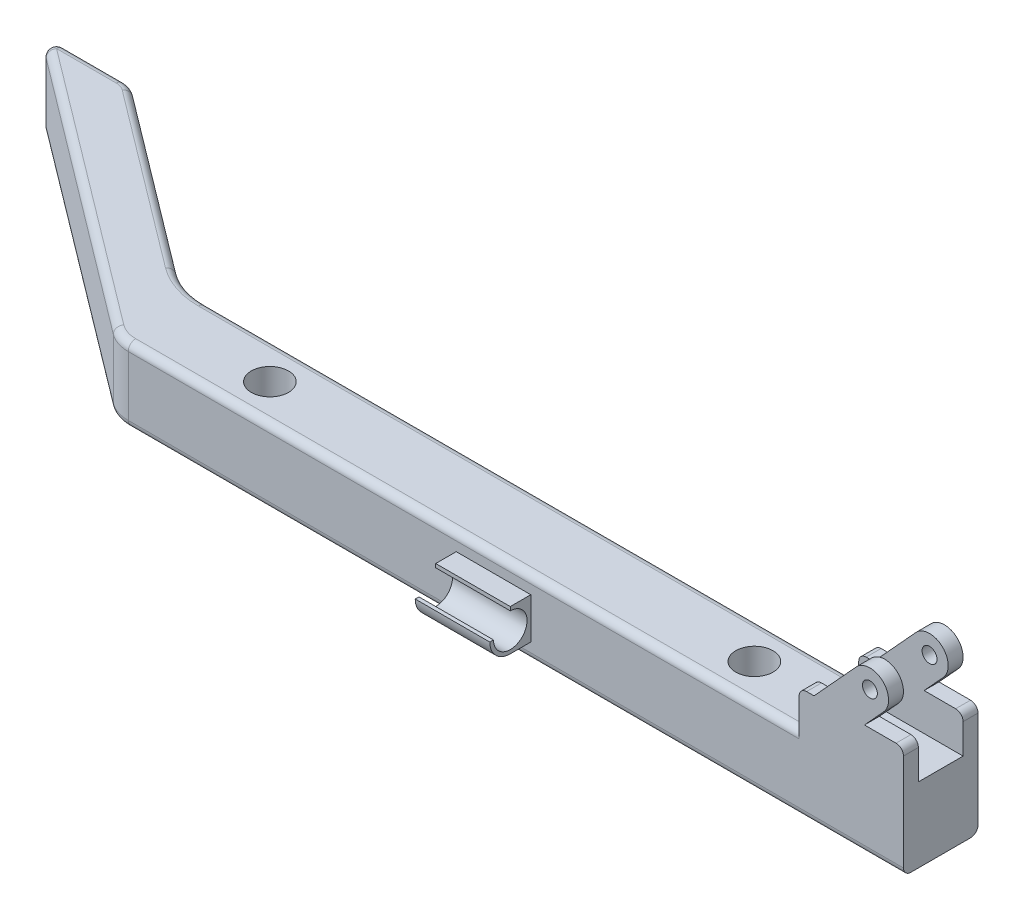
SolidWorks part; units mm, degrees
ref_plane "Front Plane" through (0, 0, 0) normal (0, 0, 1) x (1, 0, 0)
ref_plane "Top Plane" through (0, 0, 0) normal (0, 1, 0) x (1, 0, 0)
ref_plane "Right Plane" through (0, 0, 0) normal (1, 0, 0) x (0, 0, -1)
sketch "Sketch1" plane through (0, 0, 0) normal (0, 1, 0) x (1, 0, 0)
  line L0 (-49, 0) -> (49, 0)
  line L1 (-52.0091, 1.0069) -> (-88.6132, 28.5908)
  line L2 (-88.0114, 30.3894) -> (-80.0038, 30.3894)
  line L3 (-78.1983, 29.7853) -> (-54.6153, 12.0137)
  line L4 (-48.5971, 10) -> (49, 10)
  line L5 (49, 10) -> (55, 10)
  line L6 (49, 0) -> (55, 0)
  line L7 (55, 0) -> (55, 10)
  arc A0 (-52.0091, 1.0069) -> (-49, 0) centre (-49, 5) ccw
  arc A1 (-48.5971, 10) -> (-54.6153, 12.0137) centre (-48.5971, 20) cw
  arc A2 (-88.6132, 28.5908) -> (-88.0114, 30.3894) centre (-88.0114, 29.3894) cw
  arc A3 (-80.0038, 30.3894) -> (-78.1983, 29.7853) centre (-80.0038, 27.3894) cw
  point P4 (0, 0)
  point P14 (-91, 30.3894)
  point P18 (-79, 30.3894)
  dimension "D2" = 10
  dimension "D3" = 42
  dimension "D5" = 10
  dimension "D7" = 1
  dimension "D8" = 3
  dimension "D9" = 5
  dimension "D1" = 98
  dimension "D4" = 10
  dimension "D6" = 12
  dimension "D10" = 37.001
  dimension "D11" = 6
extrude "Boss-Extrude2" add sketch "Sketch1" along normal mid plane 10
sketch "Sketch3" plane through (0, 0, 0) normal (0, 0, 1) x (1, 0, 0)
  line L10 (-49, 5) -> (55, 5) construction
  line L19 (41, 5) -> (55, 5)
  line L21 (41, 5) -> (55, 5)
  line L22 (41, 5) -> (41, 10)
  line L23 (41, 10) -> (55, 10)
  line L24 (55, 5) -> (55, 10)
  line L25 (43, 10) -> (53, 10)
  line L26 (43, 10) -> (43, 17)
  line L27 (43, 17) -> (53, 17)
  line L28 (53, 10) -> (53, 17)
  dimension "D2" = 5
  dimension "D3" = 14
  dimension "D4" = 7
  dimension "D5" = 10
  dimension "D11" = 2
extrude "Boss-Extrude3" add sketch "Sketch3" against normal blind 2 contours L19 L24 L23 L22 | L23 L28 L27 L26
sketch "Sketch4" plane through (0, 0, 0) normal (0, 0, 1) x (1, 0, 0)
  line L8 (41, 10) -> (43, 10) construction
  line L9 (41, 5) -> (41, 10) construction
  line L13 (55, 10) -> (55, -5) construction
  line L14 (53, 10) -> (55, 10) construction
  line L16 (53, 10) -> (53, 17) construction
  line L17 (43, 17) -> (53, 17) construction
  line L18 (43, 10) -> (43, 17) construction
  line L19 (42, 10) -> (43, 10)
  line L20 (41, 5) -> (41, 9)
  line L21 (55, 9) -> (55, -5)
  line L22 (53, 10) -> (54, 10)
  line L23 (53, 10) -> (53, 17)
  line L24 (43, 17) -> (53, 17)
  line L25 (43, 10) -> (43, 17)
  line L26 (43, 10) -> (53, 10)
  line L28 (50.5, 14.5) -> (48.7322, 16.2678) construction
  line L31 (50.5, 14.5) -> (52.2678, 12.7322) construction
  line L32 (48.7322, 16.2678) -> (43, 10)
  line L34 (52.2678, 12.7322) -> (49.769, 10)
  arc A4 (55, 9) -> (54, 10) centre (54, 9) ccw
  arc A5 (42, 10) -> (41, 9) centre (42, 9) ccw
  circle A8 centre (50.5, 14.5) radius 2.5
  circle A9 centre (50.5, 14.5) radius 1
  dimension "D2" = 5
  dimension "D4" = 2
  dimension "D1" = 1
  dimension "D3" = 45
extrude "Cut-Extrude1" cut sketch "Sketch4" against normal through all
ref_plane "Plane1" through (0, 0, -5) normal (0, 0, 1) x (1, 0, 0)
mirror "Mirror1" about plane through (0, 0, -5) normal (0, 0, 1) of "Boss-Extrude3", "Cut-Extrude1"
fillet "Fillet1" radius 1 9 edges at (3, -5, 0) (-50.5866, -5, -0.2584) (-70.3112, -5, -14.7988) (-88.9597, -5, -29.7067) (-84.0076, -5, -30.3894) (-79.0519, -5, -30.2344) (-66.4068, -5, -20.8995) (-51.7702, -5, -10.5168) (3.2015, -5, -10)
fillet "Fillet2" radius 1 9 edges at (-3.7985, 5, -10) (-51.7702, 5, -10.5168) (-66.4068, 5, -20.8995) (-79.0519, 5, -30.2344) (-84.0076, 5, -30.3894) (-88.9597, 5, -29.7067) (-70.3112, 5, -14.7988) (-50.5866, 5, -0.2584) (-4, 5, 0)
sketch "Sketch5" plane through (0, -5, 0) normal (0, -1, 0) x (1, 0, 0)
  line L0 (55, -1) -> (55, -9) construction
  line L1 (-48.5971, -9) -> (55, -9) construction
  circle A0 centre (-35, -5) radius 2.5
  circle A1 centre (30, -5) radius 2.5
  dimension "D1" = 5
  dimension "D2" = 5
  dimension "D3" = 25
  dimension "D4" = 65
  dimension "D5" = 4
extrude "Cut-Extrude2" cut sketch "Sketch5" against normal through all
sketch "Sketch8" plane through (0, 0, 0) normal (1, 0, 0) x (0, 0, -1)
  line L0 (0, 9) -> (0, -4) construction
  line L1 (0, 2.75) -> (0, -2.75)
  line L2 (-2.75, -2.75) -> (0, -2.75)
  line L3 (-2.75, 2.75) -> (0, 2.75)
  line L4 (-2.75, 0) -> (-2.75, 4.4104) construction
  line L6 (-2.75, 0) -> (-6.0184, 0) construction
  line L8 (-5, 0) -> (-5.5, 0)
  line L9 (-2.75, 2.75) -> (-2.75, 2.25)
  arc A1 (-2.75, -2.25) -> (-2.75, 2.25) centre (-2.75, 0) ccw
  arc A2 (-2.75, -2.25) -> (-5, 0) centre (-2.75, 0) cw
  arc A3 (-2.75, -2.75) -> (-5.5, 0) centre (-2.75, 0) cw
  dimension "D1" = 5.5
  dimension "D2" = 4.5
  dimension "D3" = 2.75
  dimension "D4" = 2.75
extrude "Boss-Extrude4" add sketch "Sketch8" along normal mid plane 10
